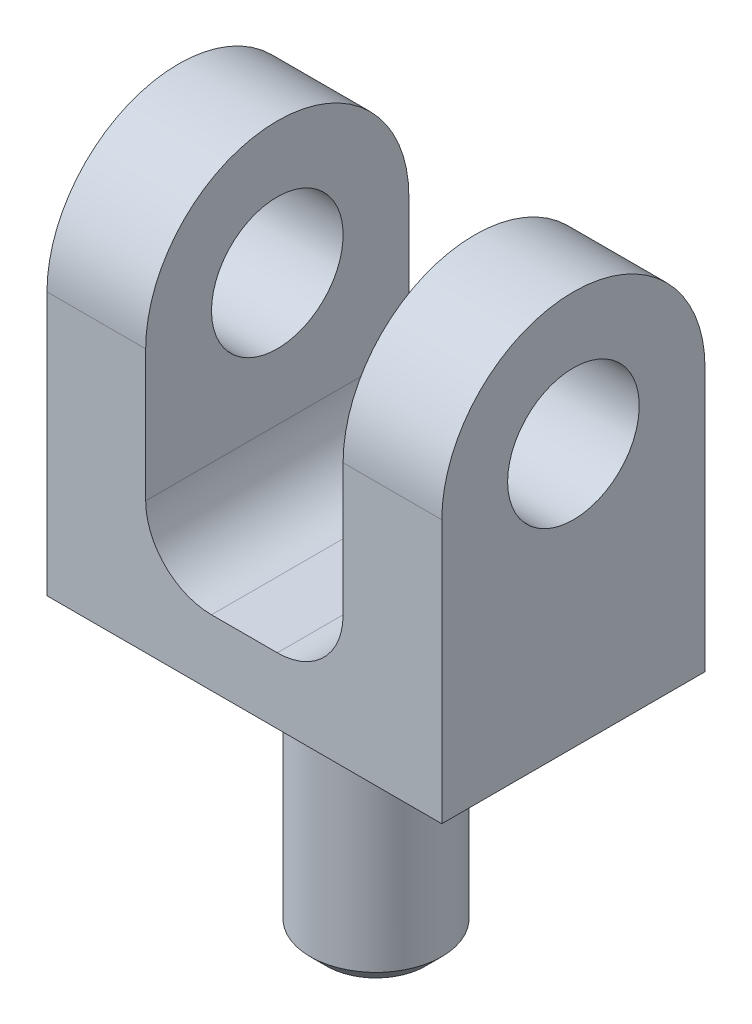
SolidWorks part; units mm, degrees
material "6061 Alloy"
ref_plane "Front Plane" through (0, 0, 0) normal (0, 0, 1) x (1, 0, 0)
ref_plane "Top Plane" through (0, 0, 0) normal (0, 1, 0) x (1, 0, 0)
ref_plane "Right Plane" through (0, 0, 0) normal (1, 0, 0) x (0, 0, -1)
sketch "Sketch1" plane through (0, 0, 0) normal (1, 0, 0) x (0, 0, -1)
  line L0 (-6.35, 0) -> (-6.35, -12.7)
  line L1 (-6.35, -12.7) -> (6.35, -12.7)
  line L2 (6.35, -12.7) -> (6.35, 0)
  line L3 (0, 0) -> (0, -12.7) construction
  circle A0 centre (0, 0) radius 3.175
  arc A1 (-6.35, 0) -> (6.35, 0) centre (0, 0) cw
  dimension "D1" = 6.35
  dimension "D2" = 6.35
  dimension "D3" = 12.7
extrude "Boss-Extrude1" add sketch "Sketch1" along normal mid plane 19.05
sketch "Sketch2" plane through (0, -12.7, 0) normal (0, -1, 0) x (1, 0, 0)
  line L0 (-9.525, 0) -> (9.525, 0) construction
  line L1 (-9.525, 6.35) -> (-9.525, -6.35) construction
  line L2 (9.525, 6.35) -> (9.525, -6.35) construction
  circle A0 centre (0, 0) radius 3.175
  dimension "D1" = 6.35
extrude "Boss-Extrude2" add sketch "Sketch2" along normal blind 12.7
chamfer "Chamfer1" distance 0.7937 angle 45 1 edges at (0, -25.4, -3.175)
sketch "Sketch3" plane through (0, 0, 0) normal (0, 0, 1) x (1, 0, 0)
  line L0 (9.525, 6.35) -> (-9.525, 6.35) construction
  line L1 (-4.7625, -9.525) -> (4.7625, -9.525)
  line L2 (-4.7625, -9.525) -> (-4.7625, 6.35)
  line L3 (-4.7625, 6.35) -> (4.7625, 6.35)
  line L4 (4.7625, -9.525) -> (4.7625, 6.35)
  line L5 (0, -9.525) -> (0, 6.35) construction
  dimension "D1" = 9.525
  dimension "D2" = 15.875
extrude "Cut-Extrude1" cut sketch "Sketch3" against normal through all and the other way through all
fillet "Fillet1" radius 3.175 2 edges at (-4.7625, -9.525, 0) (4.7625, -9.525, 0)
